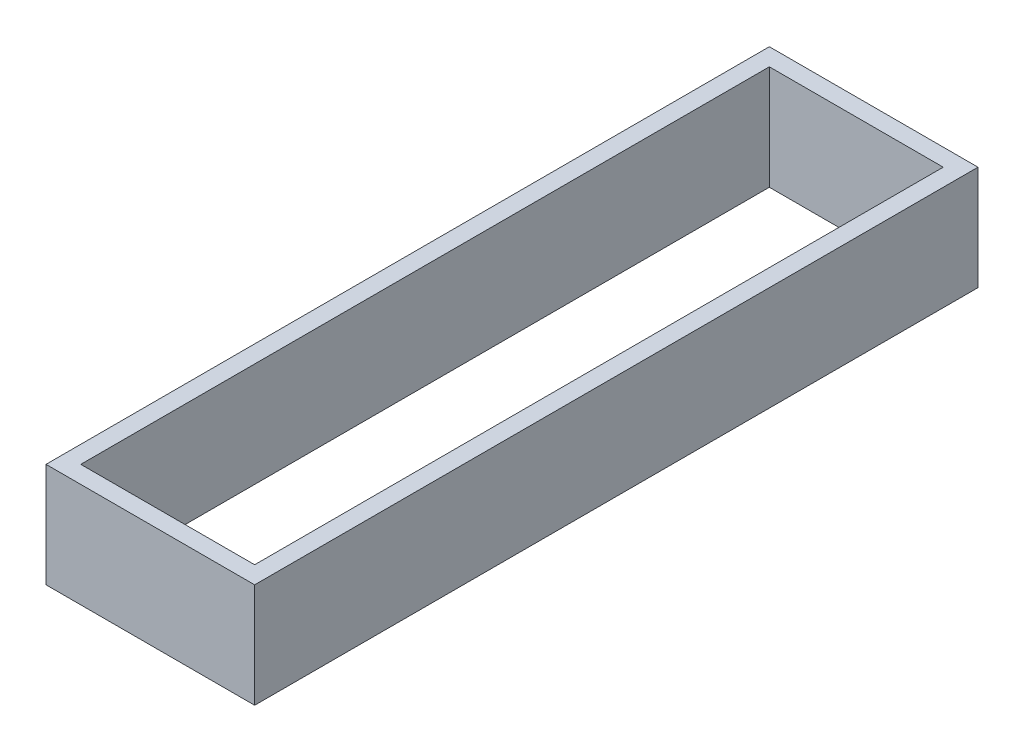
SolidWorks part; units mm, degrees
ref_plane "Front" through (0, 0, 0) normal (0, 0, 1) x (1, 0, 0)
ref_plane "Top" through (0, 0, 0) normal (0, 1, 0) x (1, 0, 0)
ref_plane "Right" through (0, 0, 0) normal (1, 0, 0) x (0, 0, -1)
sketch "ｽｹｯﾁ1" plane through (0, 0, 0) normal (0, 1, 0) x (1, 0, 0)
  line L0 (-25, -99) -> (-25, 99)
  line L1 (-30, -104) -> (30, -104)
  line L2 (-30, -104) -> (-30, 104)
  line L3 (-30, 104) -> (30, 104)
  line L4 (30, -104) -> (30, 104)
  line L5 (0, 104) -> (0, -104) construction
  line L6 (-30, 0) -> (30, 0) construction
  line L7 (-25, 99) -> (25, 99)
  line L8 (25, -99) -> (25, 99)
  line L9 (-25, -99) -> (25, -99)
  point P0 (0, 0)
  dimension "D1" = 60
  dimension "D2" = 208
  dimension "D3" = 5
extrude "ﾎﾞｽ - 押し出し1" add sketch "ｽｹｯﾁ1" along normal blind 30
ref_plane "平面1" through (0, 20, 0) normal (0, 1, 0) x (1, 0, 0)
